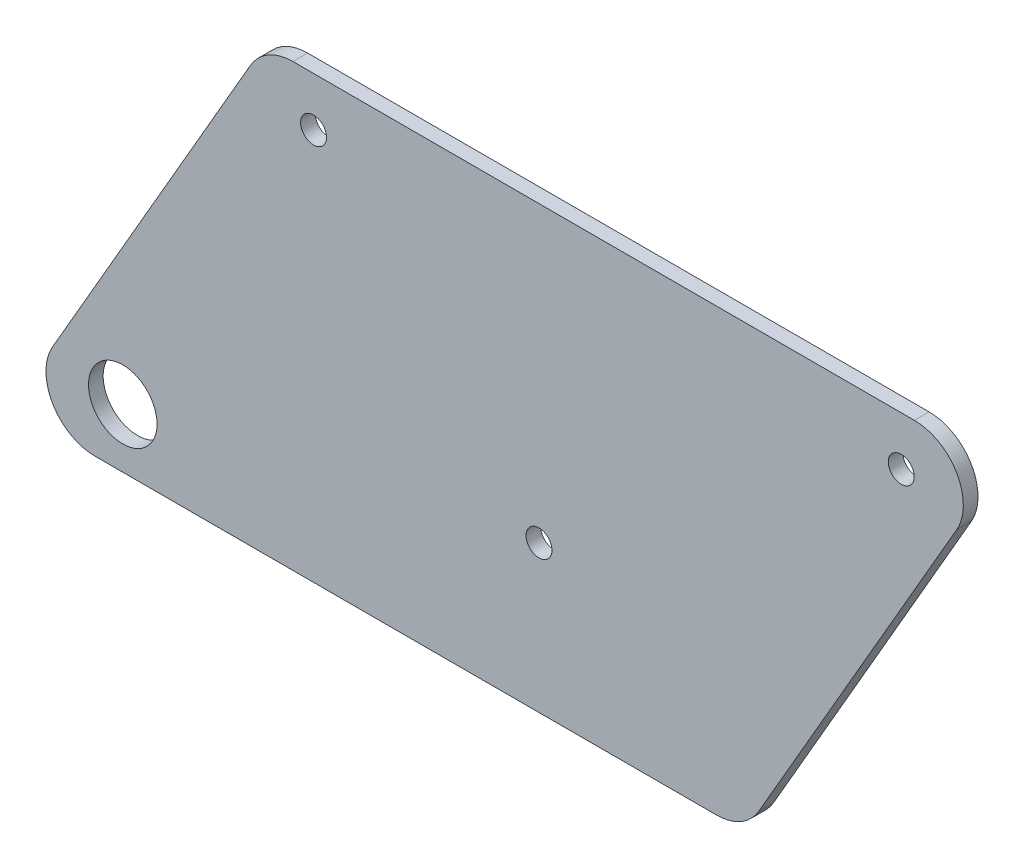
SolidWorks part; units mm, degrees
ref_plane "Front Plane" through (0, 0, 0) normal (0, 0, 1) x (1, 0, 0)
ref_plane "Top Plane" through (0, 0, 0) normal (0, 1, 0) x (1, 0, 0)
ref_plane "Right Plane" through (0, 0, 0) normal (1, 0, 0) x (0, 0, -1)
sketch "Sketch1" plane through (0, 0, 0) normal (0, 0, 1) x (1, 0, 0)
  line L0 (0, 0) -> (51.9615, 90)
  line L1 (51.9615, 90) -> (201.9615, 90)
  line L2 (201.9615, 90) -> (150, 0)
  line L3 (150, 0) -> (0, 0)
  line L4 (0, 0) -> (170.0289, 0) construction
  dimension "D1" = 90
  dimension "D2" = 60
  dimension "D3" = 150
extrude "Boss-Extrude1" add sketch "Sketch1" along normal blind 3
sketch "Sketch2" plane through (0, 0, 3) normal (0, 0, 1) x (1, 0, 0)
  line L0 (0, 0) -> (150, 0) construction
  line L1 (201.9615, 90) -> (51.9615, 90) construction
  circle A0 centre (23, 12) radius 7
  circle A1 centre (108, 30) radius 2.65
  circle A2 centre (61.9615, 80) radius 2.65
  circle A3 centre (181.9615, 80) radius 2.65
  dimension "D1" = 5.3
  dimension "D2" = 5.3
  dimension "D3" = 5.3
  dimension "D4" = 14
  dimension "D5" = 12
  dimension "D6" = 23
  dimension "D7" = 10
  dimension "D8" = 10
  dimension "D9" = 10
  dimension "D10" = 20
  dimension "D11" = 30
  dimension "D12" = 42
extrude "Cut-Extrude1" cut sketch "Sketch2" against normal blind 3
fillet "Fillet1" radius 10 4 edges at (150, 0, 1.5) (201.9615, 90, 1.5) (51.9615, 90, 1.5) (0, 0, 1.5)
